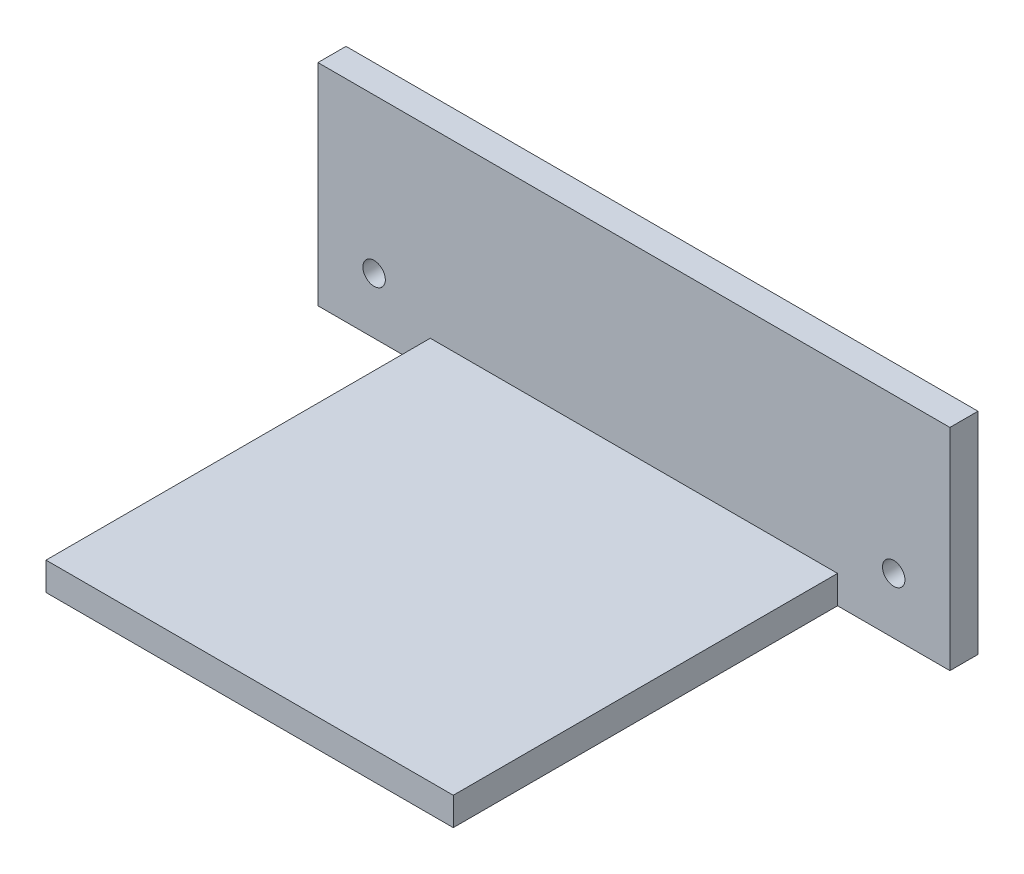
SolidWorks part; units mm, degrees
ref_plane "Front Plane" through (0, 0, 0) normal (0, 0, 1) x (1, 0, 0)
ref_plane "Top Plane" through (0, 0, 0) normal (0, 1, 0) x (1, 0, 0)
ref_plane "Right Plane" through (0, 0, 0) normal (1, 0, 0) x (0, 0, -1)
sketch "Sketch2" plane through (0, 0, 0) normal (0, 1, 0) x (1, 0, 0)
  line L0 (-38.8972, 0) -> (-9.8972, 0)
  line L1 (-38.8972, 0) -> (-38.8972, -27.475)
  line L2 (-38.8972, -27.475) -> (-9.8972, -27.475)
  line L3 (-9.8972, -27.475) -> (-9.8972, 0)
extrude "Boss-Extrude1" add sketch "Sketch2" along normal blind 2
sketch "Sketch7" plane through (0, 0, 0) normal (0, -1, 0) x (-1, 0, 0)
  line L0 (1.8972, -0.1133) -> (46.8972, -0.1133)
  line L1 (1.8972, -0.1133) -> (1.8972, 1.8867)
  line L2 (46.8972, -0.1133) -> (46.8972, 1.8867)
  line L3 (1.8972, 1.8867) -> (46.8972, 1.8867)
  point P0 (47.8801, 1.0591)
  dimension "D1" = 45
  dimension "D2" = 8
extrude "Boss-Extrude2" add sketch "Sketch7" against normal blind 15 contours L1 L3 L2 L0
hole_wizard "Tap Drill for M2x0.4 Tap1" positions "Sketch8" profile "Sketch9" hole size "M2x0.4" standard "ANSI Metric" end condition through all
sketch "Sketch8" plane through (0, 0, 0.1133) normal (0, 0, 1) x (1, 0, 0)
  line L0 (-46.8972, 15) -> (-46.8972, 0) construction
  line L1 (-38.8972, 0) -> (-46.8972, 0) construction
  point P0 (-42.8972, 4)
  dimension "D1" = 4
  dimension "D2" = 4
sketch "Sketch9" plane through (-42.8972, 4, 0.1133) normal (1, 0, 0) x (0, -1, 0)
  line L0 (0, 0) -> (0, 2)
  line L1 (0, 2) -> (0.8, 2)
  line L2 (0.8, 2) -> (0.8, 0)
  line L5 (0.8, 0) -> (0, 0)
  line L11 (0, -6.35) -> (0, 107.95) construction
  dimension "Thru Hole Dia." = 1.6
  dimension "Thru Hole Depth" = 2
hole_wizard "Tap Drill for M2x0.4 Tap2" positions "Sketch10" profile "Sketch11" hole size "M2x0.4" standard "ANSI Metric" end condition through all
sketch "Sketch10" plane through (0, 0, 0.1133) normal (0, 0, 1) x (1, 0, 0)
  line L0 (-1.8972, 15) -> (-1.8972, 0) construction
  line L1 (-1.8972, 0) -> (-9.8972, 0) construction
  point P0 (-5.8972, 4)
  dimension "D1" = 4
  dimension "D2" = 4
sketch "Sketch11" plane through (-5.8972, 4, 0.1133) normal (1, 0, 0) x (0, -1, 0)
  line L0 (0, 0) -> (0, 2)
  line L1 (0, 2) -> (0.8, 2)
  line L2 (0.8, 2) -> (0.8, 0)
  line L5 (0.8, 0) -> (0, 0)
  line L11 (0, -6.35) -> (0, 107.95) construction
  dimension "Thru Hole Dia." = 1.6
  dimension "Thru Hole Depth" = 2
